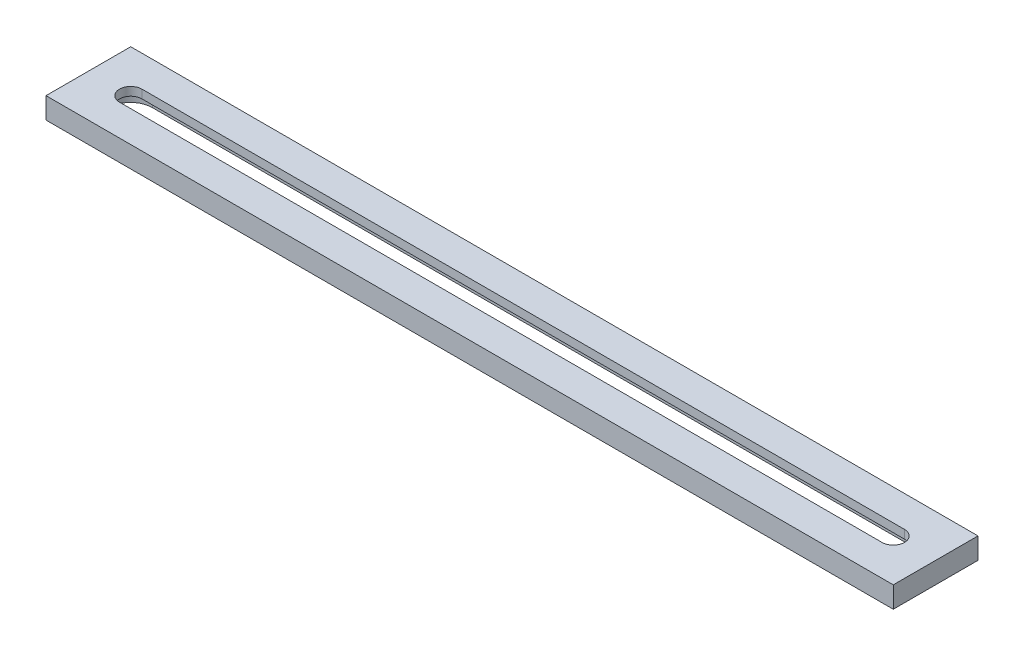
SolidWorks part; units mm, degrees
ref_plane "Front Plane" through (0, 0, 0) normal (0, 0, 1) x (1, 0, 0)
ref_plane "Top Plane" through (0, 0, 0) normal (0, 1, 0) x (1, 0, 0)
ref_plane "Right Plane" through (0, 0, 0) normal (1, 0, 0) x (0, 0, -1)
sketch "Sketch1" plane through (0, 0, 0) normal (0, 1, 0) x (1, 0, 0)
  line L1 (-127, -12.7) -> (127, -12.7)
  line L2 (-127, -12.7) -> (-127, 12.7)
  line L3 (-127, 12.7) -> (127, 12.7)
  line L4 (127, -12.7) -> (127, 12.7)
  line L5 (-127, -12.7) -> (127, 12.7) construction
  line L6 (-127, 12.7) -> (127, -12.7) construction
  point P0 (0, 0)
  dimension "D1" = 254
  dimension "D2" = 25.4
extrude "Boss-Extrude1" add sketch "Sketch1" along normal blind 6.35
sketch "Sketch2" plane through (0, 6.35, 0) normal (0, 1, 0) x (1, 0, 0)
  line L0 (-127, 0) -> (127, 0) construction
  line L1 (-127, 12.7) -> (-127, -12.7) construction
  line L2 (127, -12.7) -> (127, 12.7) construction
  line L3 (-114.3, 0) -> (114.3, 0) construction
  line L4 (-114.3, 3.3782) -> (114.3, 3.3782)
  line L5 (-114.3, -3.3782) -> (114.3, -3.3782)
  arc A0 (-114.3, 3.3782) -> (-114.3, -3.3782) centre (-114.3, 0) ccw
  arc A1 (114.3, -3.3782) -> (114.3, 3.3782) centre (114.3, 0) ccw
  point P8 (0, 0)
  dimension "D1" = 6.7564
  dimension "D2" = 228.6
extrude "Cut-Extrude1" cut sketch "Sketch2" against normal through all
sketch "Sketch3" plane through (0, 0, 0) normal (0, -1, 0) x (1, 0, 0)
  line L0 (-114.3, 0) -> (114.3, 0) construction
  line L1 (-114.3, 6.477) -> (114.3, 6.477)
  line L2 (-114.3, -6.477) -> (114.3, -6.477)
  arc A0 (-114.3, 6.477) -> (-114.3, -6.477) centre (-114.3, 0) ccw
  arc A1 (114.3, -6.477) -> (114.3, 6.477) centre (114.3, 0) ccw
  point P2 (0, 0)
  dimension "D1" = 12.954
extrude "Cut-Extrude2" cut sketch "Sketch3" against normal blind 3.81
